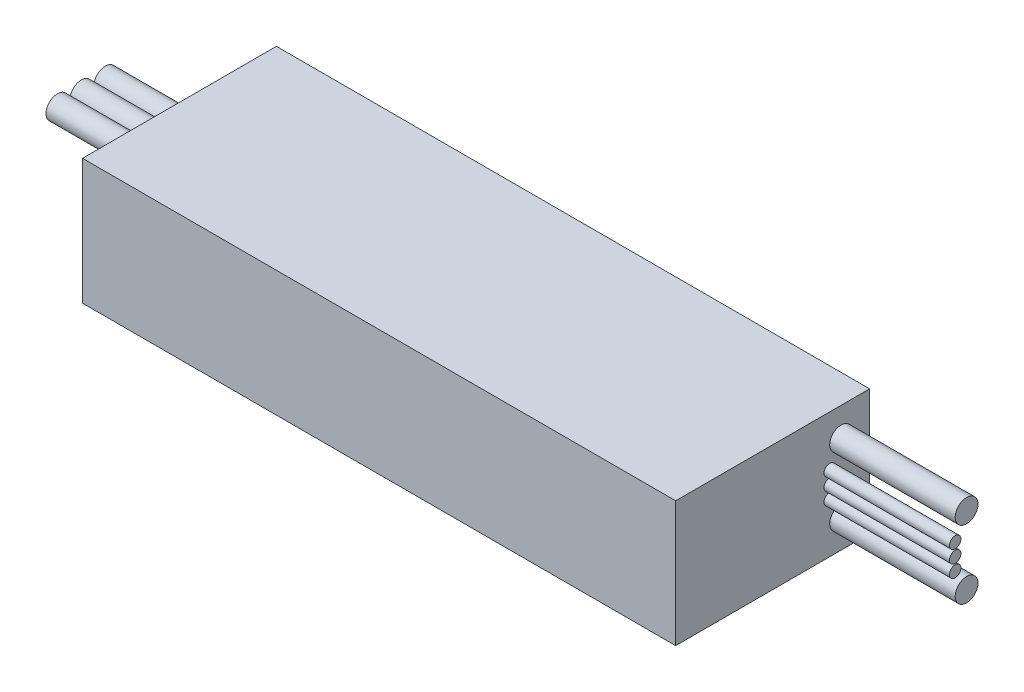
SolidWorks part; units mm, degrees
ref_plane "Front Plane" through (0, 0, 0) normal (0, 0, 1) x (1, 0, 0)
ref_plane "Top Plane" through (0, 0, 0) normal (0, 1, 0) x (1, 0, 0)
ref_plane "Right Plane" through (0, 0, 0) normal (1, 0, 0) x (0, 0, -1)
sketch "Sketch1" plane through (0, 0, 0) normal (0, 1, 0) x (1, 0, 0)
  line L1 (0, 0) -> (52, 0)
  line L2 (0, 0) -> (0, 17)
  line L3 (0, 17) -> (52, 17)
  line L4 (52, 0) -> (52, 17)
  dimension "D1" = 52
  dimension "D2" = 17
extrude "Boss-Extrude1" add sketch "Sketch1" along normal blind 11
sketch "Sketch2" plane through (0, 0, 0) normal (-1, 0, 0) x (0, 0, 1)
  line L0 (-13, 5) -> (-10.9, 5) construction
  line L1 (-10.9, 5) -> (-8.8, 5) construction
  line L2 (-17, 0) -> (0, 0) construction
  line L3 (-17, 11) -> (-17, 0) construction
  circle A0 centre (-13, 5) radius 1
  circle A1 centre (-10.9, 5) radius 1
  circle A2 centre (-8.8, 5) radius 1
  dimension "D1" = 2
  dimension "D2" = 2.1
  dimension "D3" = 2.1
  dimension "D4" = 5
  dimension "D5" = 4
extrude "Boss-Extrude2" add sketch "Sketch2" along normal blind 11
sketch "Sketch3" plane through (52, 0, 0) normal (1, 0, 0) x (0, 0, -1)
  line L0 (13.5, 6.6) -> (13.5, 5.5) construction
  line L1 (13.5, 5.5) -> (13.5, 4.4) construction
  line L2 (14.5, 8.5) -> (14.5, 2.5) construction
  line L3 (17, 11) -> (17, 0) construction
  line L4 (0, 11) -> (17, 11) construction
  circle A0 centre (14.5, 8.5) radius 1
  circle A1 centre (14.5, 2.5) radius 1
  circle A2 centre (13.5, 6.6) radius 0.5
  circle A3 centre (13.5, 5.5) radius 0.5
  circle A4 centre (13.5, 4.4) radius 0.5
  point P14 (14.5, 5.5)
  dimension "D1" = 1
  dimension "D2" = 1.1
  dimension "D3" = 2
  dimension "D4" = 2.5
  dimension "D5" = 3.5
  dimension "D6" = 5.5
  dimension "D7" = 5.5
  dimension "D8" = 6
extrude "Boss-Extrude3" add sketch "Sketch3" along normal blind 11
